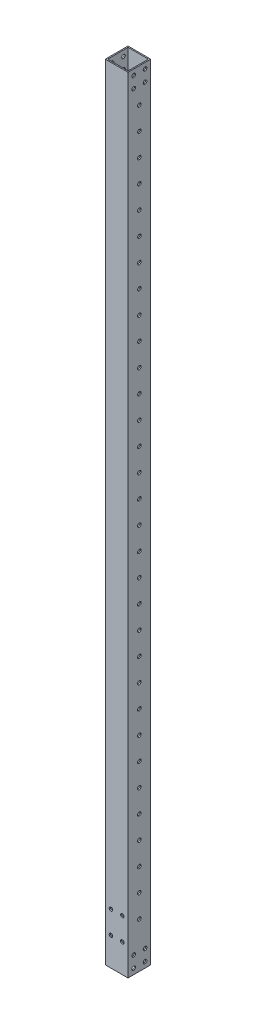
SolidWorks part; units mm, degrees
ref_plane "前视基准面" through (0, 0, 0) normal (0, 0, 1) x (1, 0, 0)
ref_plane "上视基准面" through (0, 0, 0) normal (0, 1, 0) x (1, 0, 0)
ref_plane "右视基准面" through (0, 0, 0) normal (1, 0, 0) x (0, 0, -1)
other "Configuration Table"
sketch "草图1" plane through (0, 0, 0) normal (0, 1, 0) x (1, 0, 0)
  line L1 (-10, -10) -> (10, -10)
  line L2 (-10, -10) -> (-10, 10)
  line L3 (-10, 10) -> (10, 10)
  line L4 (10, -10) -> (10, 10)
  line L5 (-10, -10) -> (10, 10) construction
  line L6 (-10, 10) -> (10, -10) construction
  point P0 (0, 0)
  dimension "D1" = 20
  dimension "D2" = 20
extrude "拉伸-薄壁1" add sketch "草图1" along normal blind 690 thin thin type one direction reverse wall 1
sketch "草图2" plane through (10, 0, 0) normal (1, 0, 0) x (0, 0, -1)
  line L0 (10, 690) -> (10, 0) construction
  line L1 (-10, 690) -> (10, 690)
  line L2 (-10, 690) -> (-10, 670)
  line L3 (-10, 670) -> (10, 670)
  line L4 (10, 690) -> (10, 670)
  line L6 (-10, 0) -> (10, 0)
  line L7 (-10, 0) -> (-10, 20)
  line L8 (-10, 20) -> (10, 20)
  line L9 (10, 0) -> (10, 20)
  dimension "D1" = 20
  dimension "D2" = 20
sketch "草图3" plane through (0, 0, 10) normal (0, 0, -1) x (-1, 0, 0)
  line L0 (0, 0) -> (0, 66.0608) construction
  line L1 (-10, 35) -> (10, 35) construction
  line L6 (-10, 690) -> (-10, 0) construction
  line L7 (10, 690) -> (10, 0) construction
  line L8 (-10, 0) -> (10, 0) construction
  circle A0 centre (-5, 25) radius 1.55
  circle A3 centre (-5, 45) radius 1.55
  circle A4 centre (5, 25) radius 1.55
  circle A5 centre (5, 45) radius 1.55
  dimension "D2" = 3.1
  dimension "D1" = 35
  dimension "D3" = 10
  dimension "D4" = 5
extrude "切除-拉伸2" cut sketch "草图3" along normal through all
sketch "草图4" plane through (10, 0, 0) normal (1, 0, 0) x (0, 0, -1)
  line L0 (-10, 10) -> (10, 10) construction
  line L1 (-10, 0) -> (-10, 20) construction
  line L2 (10, 0) -> (10, 20) construction
  line L3 (0, 0) -> (0, 20) construction
  line L4 (-10, 20) -> (10, 20) construction
  line L5 (10, 345) -> (-10, 345) construction
  line L6 (10, 690) -> (10, 0) construction
  line L7 (-10, 690) -> (-10, 0) construction
  line L8 (0, 690) -> (0, 670) construction
  line L9 (-10, 680) -> (10, 680) construction
  circle A0 centre (-5, 5) radius 1.6
  circle A1 centre (-5, 15) radius 1.6
  circle A2 centre (5, 5) radius 1.6
  circle A3 centre (5, 15) radius 1.6
  circle A4 centre (5, 675) radius 1.6
  circle A5 centre (5, 685) radius 1.6
  circle A6 centre (-5, 675) radius 1.6
  circle A7 centre (-5, 685) radius 1.6
  dimension "D1" = 3.2
  dimension "D2" = 5
  dimension "D3" = 5
extrude "切除-拉伸3" cut sketch "草图4" against normal through all
sketch "草图5" plane through (10, 0, 0) normal (1, 0, 0) x (0, 0, -1)
  line L0 (-10, 0) -> (10, 0) construction
  line L1 (0, 60) -> (0, 0) construction
  circle A0 centre (0, 60) radius 1.6
  circle A1 centre (0, 80) radius 1.6
  circle A2 centre (0, 100) radius 1.6
  circle A3 centre (0, 120) radius 1.6
  circle A4 centre (0, 140) radius 1.6
  circle A5 centre (0, 160) radius 1.6
  circle A6 centre (0, 180) radius 1.6
  circle A7 centre (0, 200) radius 1.6
  circle A8 centre (0, 220) radius 1.6
  circle A9 centre (0, 240) radius 1.6
  circle A10 centre (0, 260) radius 1.6
  circle A11 centre (0, 280) radius 1.6
  circle A12 centre (0, 300) radius 1.6
  circle A13 centre (0, 320) radius 1.6
  circle A14 centre (0, 340) radius 1.6
  circle A15 centre (0, 360) radius 1.6
  circle A16 centre (0, 380) radius 1.6
  circle A17 centre (0, 400) radius 1.6
  circle A18 centre (0, 420) radius 1.6
  circle A19 centre (0, 440) radius 1.6
  circle A20 centre (0, 460) radius 1.6
  circle A21 centre (0, 480) radius 1.6
  circle A22 centre (0, 500) radius 1.6
  circle A23 centre (0, 520) radius 1.6
  circle A24 centre (0, 540) radius 1.6
  circle A25 centre (0, 560) radius 1.6
  circle A26 centre (0, 580) radius 1.6
  circle A27 centre (0, 600) radius 1.6
  circle A28 centre (0, 620) radius 1.6
  circle A29 centre (0, 640) radius 1.6
  circle A30 centre (0, 660) radius 1.6
  circle A31 centre (0, 40) radius 1.6
  dimension "D1" = 3.2
  dimension "D2" = 60
  dimension "D3" = 30
  dimension "D4" = 2
  dimension "D5" = 2
extrude "切除-拉伸4" cut sketch "草图5" against normal through all
